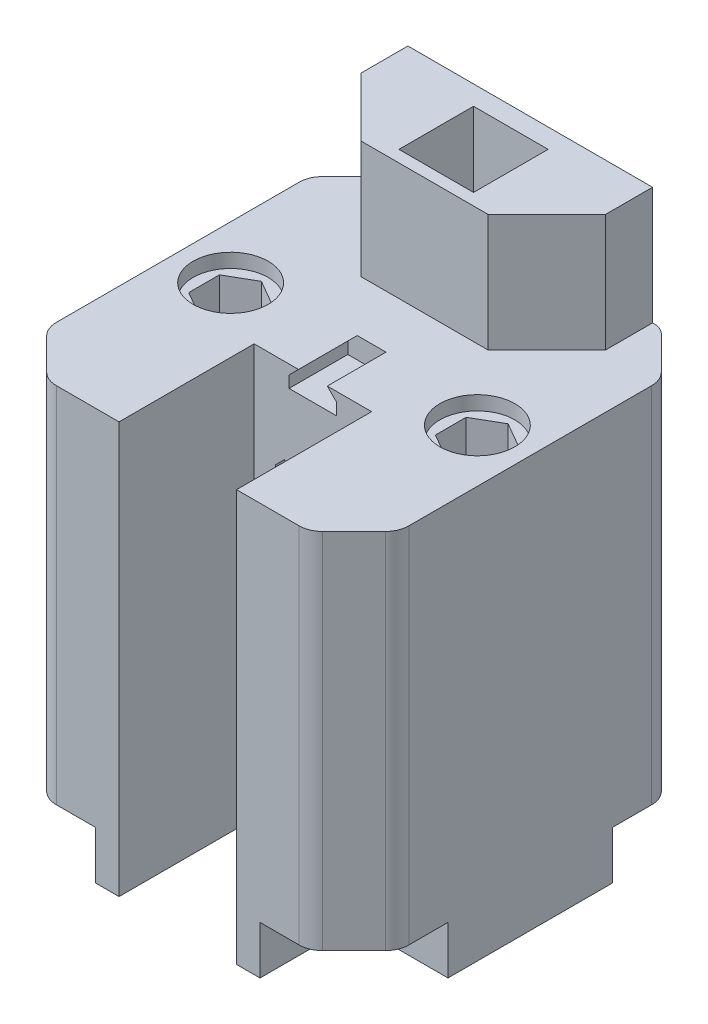
SolidWorks part; units mm, degrees
ref_plane "前视基准面" through (0, 0, 0) normal (0, 0, 1) x (1, 0, 0)
ref_plane "上视基准面" through (0, 0, 0) normal (0, 1, 0) x (1, 0, 0)
ref_plane "右视基准面" through (0, 0, 0) normal (1, 0, 0) x (0, 0, -1)
sketch "草图1" plane through (0, 0, 0) normal (0, 1, 0) x (1, 0, 0)
  line L0 (0, 0) -> (29, 0) construction
  line L1 (0, 0) -> (22.981, -22.981) construction
  line L2 (-29, 11.25) -> (-29, -11.25) construction
  line L3 (-30.9359, 15.026) -> (-15.026, 30.9359) construction
  line L4 (-22.981, 22.981) -> (0, 0) construction
  line L5 (-29, 0) -> (0, 0) construction
  line L6 (-40.25, 21.6218) -> (-40.25, -21.6218) construction
  line L7 (-40.25, 21.6218) -> (-21.6218, 40.25) construction
  line L8 (-22.981, 22.981) -> (-30.9359, 30.9359) construction
  line L9 (-29, 0) -> (-40.25, 0) construction
  line L10 (21.6218, 40.25) -> (40.25, 21.6218) construction
  line L11 (21.6218, 40.25) -> (-21.6218, 40.25) construction
  line L12 (40.25, -21.6218) -> (21.6218, -40.25) construction
  line L13 (40.25, -21.6218) -> (40.25, 21.6218) construction
  line L14 (-21.6218, -40.25) -> (-40.25, -21.6218) construction
  line L15 (-21.6218, -40.25) -> (21.6218, -40.25) construction
  line L16 (22.8645, 43.25) -> (-22.8645, 43.25)
  line L17 (-43.25, 22.8645) -> (-22.8645, 43.25)
  line L18 (-43.25, 22.8645) -> (-43.25, -22.8645)
  line L19 (-22.8645, -43.25) -> (-43.25, -22.8645)
  line L20 (-22.8645, -43.25) -> (22.8645, -43.25)
  line L21 (43.25, -22.8645) -> (22.8645, -43.25)
  line L22 (43.25, -22.8645) -> (43.25, 22.8645)
  line L23 (22.8645, 43.25) -> (43.25, 22.8645)
  line L24 (10.8523, 14.25) -> (-10.8523, 14.25)
  line L25 (-14.25, 10.8523) -> (-10.8523, 14.25)
  line L26 (-14.25, 10.8523) -> (-14.25, -10.8523)
  line L27 (-10.8523, -14.25) -> (-14.25, -10.8523)
  line L28 (-10.8523, -14.25) -> (10.8523, -14.25)
  line L29 (14.25, -10.8523) -> (10.8523, -14.25)
  line L30 (14.25, -10.8523) -> (14.25, 10.8523)
  line L31 (10.8523, 14.25) -> (14.25, 10.8523)
  circle A0 centre (0, 0) radius 14.25 construction
  circle A1 centre (29, 0) radius 11.25 construction
  circle A2 centre (22.981, -22.981) radius 11.25 construction
  circle A3 centre (0, -29) radius 11.25 construction
  circle A4 centre (-22.981, -22.981) radius 11.25 construction
  circle A5 centre (-29, 0) radius 11.25 construction
  circle A6 centre (-22.981, 22.981) radius 11.25 construction
  circle A7 centre (0, 29) radius 11.25 construction
  circle A8 centre (22.981, 22.981) radius 11.25 construction
  point P22 (0, 0)
  point P41 (0, 0)
  dimension "D1" = 28.5
  dimension "D2" = 22.5
  dimension "D3" = 29
  dimension "D4" = 32.5
  dimension "D5" = 45
  dimension "D8" = 3
  dimension "D9" = 26
  dimension "D6" = 4
  dimension "D7" = 4
sketch "草图3" plane through (0, 0, 0) normal (0, 1, 0) x (1, 0, 0)
  line L32 (11.163, -15) -> (15, -11.163)
  line L33 (-11.163, -15) -> (11.163, -15)
  line L34 (-15, -11.163) -> (-11.163, -15)
  line L35 (-15, 11.163) -> (-15, -11.163)
  line L36 (-11.163, 15) -> (-15, 11.163)
  line L37 (11.163, 15) -> (-11.163, 15)
  line L38 (15, 11.163) -> (11.163, 15)
  line L39 (15, -11.163) -> (15, 11.163)
  line L40 (11.163, -15) -> (15, -11.163)
  line L41 (-11.163, -15) -> (11.163, -15)
  line L42 (-15, -11.163) -> (-11.163, -15)
  line L43 (-15, 11.163) -> (-15, -11.163)
  line L44 (-11.163, 15) -> (-15, 11.163)
  line L45 (11.163, 15) -> (-11.163, 15)
  line L46 (15, 11.163) -> (11.163, 15)
  line L47 (15, -11.163) -> (15, 11.163)
  dimension "D1" = 0.75
extrude "凸台-拉伸1" add sketch "草图3" along normal blind 35
sketch "草图4" plane through (0, 35, 0) normal (0, 1, 0) x (1, 0, 0)
  line L0 (0, 0) -> (10.5, 0) construction
  line L1 (0, 0) -> (29, 0) construction
  line L2 (0, 0) -> (0, 15.9575) construction
  circle A0 centre (10.5, 0) radius 1.375
  circle A1 centre (-10.5, 0) radius 1.375
  dimension "D1" = 2.75
  dimension "D2" = 21
extrude "切除-拉伸1" cut sketch "草图4" against normal through all
sketch "草图5" plane through (0, 35, 0) normal (0, 1, 0) x (1, 0, 0)
  line L0 (0, 0) -> (0, -16.278) construction
  line L1 (-11.163, -15) -> (11.163, -15) construction
  line L2 (-5, -3.5) -> (5, -3.5)
  line L3 (-5, -3.5) -> (-5, -15)
  line L4 (-5, -15) -> (5, -15)
  line L5 (5, -3.5) -> (5, -15)
  line L6 (-5, -3.5) -> (5, -15) construction
  line L7 (-5, -15) -> (5, -3.5) construction
  point P3 (0, -9.25)
  dimension "D1" = 10
  dimension "D2" = 11.5
extrude "切除-拉伸2" cut sketch "草图5" against normal through all
sketch "草图6" plane through (0, 35, 0) normal (0, 1, 0) x (1, 0, 0)
  line L0 (0, 0) -> (0, 15) construction
  line L1 (11.163, 15) -> (-11.163, 15) construction
  line L3 (-10.413, 6) -> (10.413, 6)
  line L4 (-10.413, 6) -> (-10.413, 15)
  line L5 (-10.413, 15) -> (10.413, 15)
  line L6 (10.413, 6) -> (10.413, 15)
  line L7 (-10.413, 6) -> (10.413, 15) construction
  line L8 (-10.413, 15) -> (10.413, 6) construction
  point P5 (0, 10.5)
  point P10 (0, 0)
  point P12 (9.8823, 15.05)
  dimension "D1" = 9
  dimension "D2" = 0.75
extrude "凸台-拉伸2" add sketch "草图6" along normal blind 10
sketch "草图7" plane through (0, 45, 0) normal (0, 1, 0) x (1, 0, 0)
  line L0 (0, 15) -> (0, 6) construction
  line L1 (10.413, 15) -> (-10.413, 15) construction
  line L2 (-10.413, 6) -> (10.413, 6) construction
  line L4 (-3.175, 7) -> (3.175, 7)
  line L5 (-3.175, 7) -> (-3.175, 13.35)
  line L6 (-3.175, 13.35) -> (3.175, 13.35)
  line L7 (3.175, 7) -> (3.175, 13.35)
  line L8 (-3.175, 7) -> (3.175, 13.35) construction
  line L9 (-3.175, 13.35) -> (3.175, 7) construction
  point P6 (0, 10.175)
  dimension "D1" = 6.35
  dimension "D2" = 1
extrude "切除-拉伸3" cut sketch "草图7" against normal blind 6.5
sketch "草图8" plane through (0, 38.5, 0) normal (0, 1, 0) x (1, 0, 0)
  line L0 (0, 13.35) -> (0, 7) construction
  line L1 (3.175, 13.35) -> (-3.175, 13.35) construction
  line L2 (-3.175, 7) -> (3.175, 7) construction
  line L3 (0, 10.175) -> (3.175, 10.175) construction
  line L4 (3.175, 7) -> (3.175, 13.35) construction
  line L5 (1.675, 8.675) -> (1.675, 11.675)
  line L6 (1.675, 11.675) -> (2.425, 12.425)
  line L7 (2.425, 12.425) -> (3.175, 11.675)
  line L8 (3.175, 11.675) -> (3.175, 8.675)
  line L9 (2.425, 7.925) -> (3.175, 8.675)
  line L10 (1.675, 8.675) -> (2.425, 7.925)
  line L11 (-1.675, 8.675) -> (-2.425, 7.925)
  line L12 (-2.425, 7.925) -> (-3.175, 8.675)
  line L13 (-3.175, 11.675) -> (-3.175, 8.675)
  line L14 (-2.425, 12.425) -> (-3.175, 11.675)
  line L15 (-1.675, 11.675) -> (-2.425, 12.425)
  line L16 (-1.675, 8.675) -> (-1.675, 11.675)
  point P17 (1.675, 10.175)
  dimension "D1" = 3
  dimension "D2" = 1.5
sketch "草图9" plane through (0, 0, 0) normal (1, 0, 0) x (0, 0, -1)
  line L0 (10.175, 38.5) -> (10.175, 33.5)
  line L1 (13.35, 38.5) -> (7, 38.5) construction
  line L2 (2.175, 25.5) -> (-3.5, 25.5)
  line L3 (-3.5, 0) -> (-3.5, 35) construction
  line L4 (-3.5, 0) -> (-3.5, 35) construction
  arc A0 (10.175, 33.5) -> (2.175, 25.5) centre (2.175, 33.5) cw
  dimension "D1" = 8
  dimension "D2" = 13
sweep "切除-扫描1" cut profiles "草图8" path "草图9"
ref_plane "基准面1" through (0, 22.5, 0) normal (0, 1, 0) x (1, 0, 0)
mirror "镜向1" about plane through (0, 22.5, 0) normal (0, 1, 0) of "切除-扫描1", "切除-拉伸3"
sketch "草图11" plane through (0, 35, 0) normal (0, 1, 0) x (1, 0, 0)
  line L0 (0, 0) -> (0, -6.1362) construction
  line L1 (10.5, 0) -> (10.5, 2.6154) construction
  line L2 (10.5, 2.6154) -> (8.235, 1.3077)
  line L3 (8.235, 1.3077) -> (8.235, -1.3077)
  line L4 (8.235, -1.3077) -> (10.5, -2.6154)
  line L5 (10.5, -2.6154) -> (12.765, -1.3077)
  line L6 (12.765, -1.3077) -> (12.765, 1.3077)
  line L7 (12.765, 1.3077) -> (10.5, 2.6154)
  line L8 (-10.5, -2.6154) -> (-12.765, -1.3077)
  line L9 (-8.235, -1.3077) -> (-10.5, -2.6154)
  line L10 (-8.235, 1.3077) -> (-8.235, -1.3077)
  line L11 (-10.5, 2.6154) -> (-8.235, 1.3077)
  line L12 (-12.765, 1.3077) -> (-10.5, 2.6154)
  line L13 (-12.765, -1.3077) -> (-12.765, 1.3077)
  circle A0 centre (10.5, 0) radius 2.265 construction
  dimension "D1" = 4.53
extrude "切除-拉伸4" cut sketch "草图11" against normal blind 5
sketch "草图12" plane through (0, 35, 0) normal (0, 1, 0) x (1, 0, 0)
  line L0 (0, 0) -> (0, -6.848) construction
  circle A0 centre (10.5, 0) radius 3.19
  circle A1 centre (-10.5, 0) radius 3.19
  dimension "D1" = 6.38
extrude "切除-拉伸5" cut sketch "草图12" against normal blind 1.2
sketch "草图13" plane through (0, 0, 3.5) normal (0, 0, 1) x (1, 0, 0)
  line L0 (0, 0) -> (0, 35) construction
  line L1 (5, 0) -> (-5, 0) construction
  line L2 (-10.413, 35) -> (10.413, 35) construction
  line L3 (5, 35) -> (-5, 35) construction
  line L4 (-2.025, 33.2) -> (2.025, 33.2)
  line L5 (-2.025, 33.2) -> (-2.025, 35)
  line L6 (-2.025, 35) -> (2.025, 35)
  line L7 (2.025, 33.2) -> (2.025, 35)
  line L8 (-2.025, 33.2) -> (2.025, 35) construction
  line L9 (-2.025, 35) -> (2.025, 33.2) construction
  point P6 (0, 34.1)
  dimension "D1" = 1.8
  dimension "D2" = 4.05
extrude "切除-拉伸6" cut sketch "草图13" against normal blind 5
sketch "草图14" plane through (0, 0, -1.5) normal (0, 0, 1) x (1, 0, 0)
  line L0 (0, 0) -> (0, 39.4946) construction
  line L1 (1.225, 35) -> (2.025, 35)
  line L2 (2.025, 35) -> (-2.025, 35) construction
  line L3 (2.025, 35) -> (2.025, 34.2)
  line L4 (2.025, 33.2) -> (2.025, 35) construction
  line L5 (2.025, 34.2) -> (1.225, 35)
  line L6 (-2.025, 34.2) -> (-1.225, 35)
  line L7 (-2.025, 35) -> (-2.025, 34.2)
  line L8 (-1.225, 35) -> (-2.025, 35)
  dimension "D1" = 45
  dimension "D2" = 0.8
extrude "凸台-拉伸3" add sketch "草图14" along normal up to surface (5 mm away) up to face at (-2.425, 19.5, 3.5)
chamfer "倒角1" distance 5 angle 45 2 edges at (10.413, 40, -6) (-10.413, 40, -6)
sketch "草图17" [suppressed] plane through (0, 35, 0) normal (0, 1, 0) x (1, 0, 0)
  line L0 (5, -14.95) -> (11.1422, -14.95)
  line L1 (11.1422, -14.95) -> (14.1422, -11.95)
  line L2 (11.1422, -14.95) -> (14.95, -11.1422) construction
  line L3 (14.1422, -11.95) -> (5, -11.95)
  line L4 (5, -14.95) -> (5, -3.45) construction
  line L5 (5, -11.95) -> (5, -14.95)
  line L6 (0, 0) -> (0, -28.1118) construction
  line L7 (-5, -11.95) -> (-5, -14.95)
  line L8 (-14.1422, -11.95) -> (-5, -11.95)
  line L9 (-11.1422, -14.95) -> (-14.1422, -11.95)
  line L10 (-5, -14.95) -> (-11.1422, -14.95)
  dimension "D1" = 3
sketch "草图18" plane through (0, 0, 0) normal (0, -1, 0) x (1, 0, 0)
  line L0 (15, 11.163) -> (15, -11.163) construction
  line L1 (7, -7) -> (15, -7)
  line L2 (7, -7) -> (7, -15)
  line L3 (7, -15) -> (15, -15)
  line L4 (15, -7) -> (15, -15)
  line L5 (11.163, -15) -> (-11.163, -15) construction
  line L6 (-7, -7) -> (-7, -15)
  line L7 (-7, -15) -> (-15, -15)
  line L8 (-15, -7) -> (-15, -15)
  line L9 (-7, -7) -> (-15, -7)
  line L10 (-7, 7) -> (-15, 7)
  line L11 (-15, 7) -> (-15, 15)
  line L12 (-7, 15) -> (-15, 15)
  line L13 (-7, 7) -> (-7, 15)
  line L14 (7, 7) -> (7, 15)
  line L15 (7, 15) -> (15, 15)
  line L16 (15, 7) -> (15, 15)
  line L17 (7, 7) -> (15, 7)
  point P23 (0, 0)
  dimension "D1" = 8
  dimension "D2" = 4
extrude "切除-拉伸7" cut sketch "草图18" against normal blind 4.1
chamfer "倒角2" distance 2.5 angle 45 4 edges at (-7, 2.05, -7) (-7, 2.05, 7) (7, 2.05, 7) (7, 2.05, -7)
ref_plane "基准面2" through (0, 17.5, 0) normal (0, 1, 0) x (1, 0, 0)
mirror "镜向2" about plane through (0, 17.5, 0) normal (0, 1, 0) of "切除-拉伸5", "切除-拉伸4"
sketch "草图19" plane through (0, 4.1, 0) normal (0, -1, 0) x (1, 0, 0)
  circle A0 centre (11, 11) radius 1.175 construction
  circle A1 centre (11, -11) radius 1.175 construction
  circle A2 centre (-11, 11) radius 1.175 construction
  circle A3 centre (-11, -11) radius 1.175 construction
  circle A4 centre (11, 11) radius 1.175 construction
  circle A5 centre (11, -11) radius 1.175 construction
  circle A6 centre (-11, 11) radius 1.175 construction
  circle A7 centre (-11, -11) radius 1.175 construction
  circle A8 centre (11, -11) radius 1.625
  circle A9 centre (-11, -11) radius 1.625
  circle A10 centre (-11, 11) radius 1.625
  circle A11 centre (11, 11) radius 1.625
  dimension "D1" = 3.25
extrude "切除-拉伸8" cut sketch "草图19" against normal blind 6
sketch "草图20" plane through (0, 0, -15) normal (0, 0, -1) x (-1, 0, 0)
  circle A0 centre (9, 40) radius 1.175 construction
  circle A1 centre (-9, 40) radius 1.175 construction
  circle A2 centre (9, 40) radius 1.175 construction
  circle A3 centre (-9, 40) radius 1.175 construction
  circle A4 centre (-9, 40) radius 1.625
  circle A5 centre (9, 40) radius 1.625
  dimension "D1" = 3.25
extrude "切除-拉伸9" [suppressed] cut sketch "草图20" against normal blind 10
fillet "圆角1" radius 2 6 edges at (15, 19.55, -11.163) (15, 19.55, 11.163) (11.163, 19.55, 15) (-11.163, 19.55, 15) (-15, 19.55, 11.163) (-15, 19.55, -11.163)
fillet "圆角2" radius 1.5 2 edges at (11.163, 19.55, -15) (-11.163, 19.55, -15)
